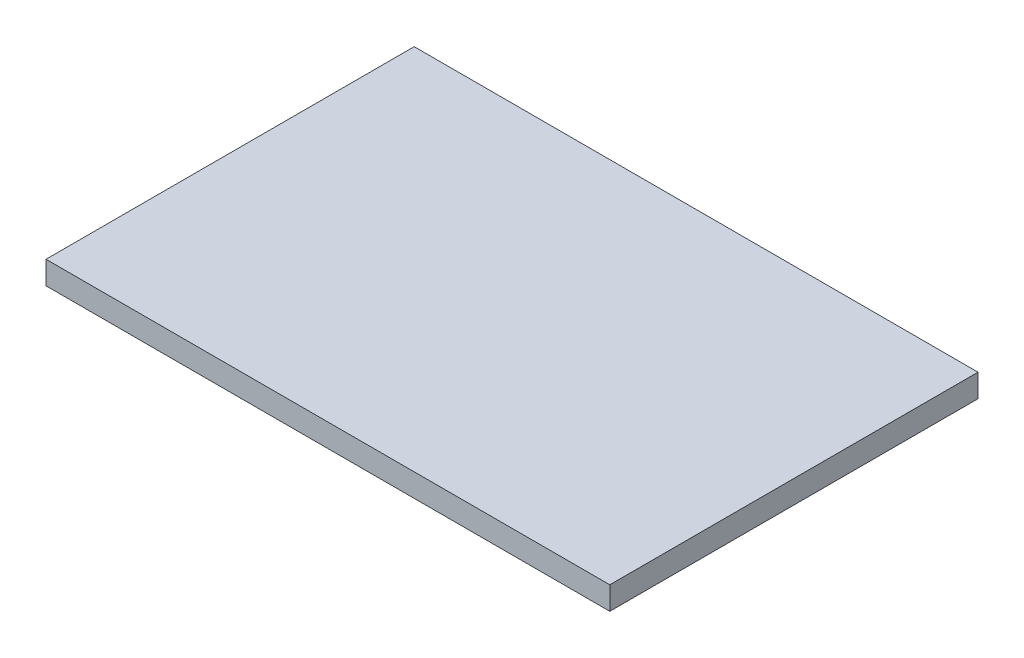
SolidWorks part; units mm, degrees
ref_plane "Front Plane" through (0, 0, 0) normal (0, 0, 1) x (1, 0, 0)
ref_plane "Top Plane" through (0, 0, 0) normal (0, 1, 0) x (1, 0, 0)
ref_plane "Right Plane" through (0, 0, 0) normal (1, 0, 0) x (0, 0, -1)
sketch "Sketch1" plane through (0, 0, 0) normal (0, 0, 1) x (1, 0, 0)
  line L1 (43.1889, 16.1056) -> (67.6889, 16.1056)
  line L2 (43.1889, 16.1056) -> (43.1889, 0.1056)
  line L3 (43.1889, 0.1056) -> (67.6889, 0.1056)
  line L4 (67.6889, 16.1056) -> (67.6889, 0.1056)
  line L5 (55.4389, 0.1056) -> (55.4389, 16.1056) construction
  line L6 (43.1889, 8.1056) -> (67.6889, 8.1056) construction
  point P104 (55.4389, 8.1056)
  dimension "D1" = 16
  dimension "D2" = 24.5
extrude "Boss-Extrude1" add sketch "Sketch1" along normal blind 1
move or copy body "Body-Move/Copy1" bodies to move or copy 102 copy no rotation origin (0, 8.1056, 0.25) rotation axis (1, 0, 0) rotation angle 90
